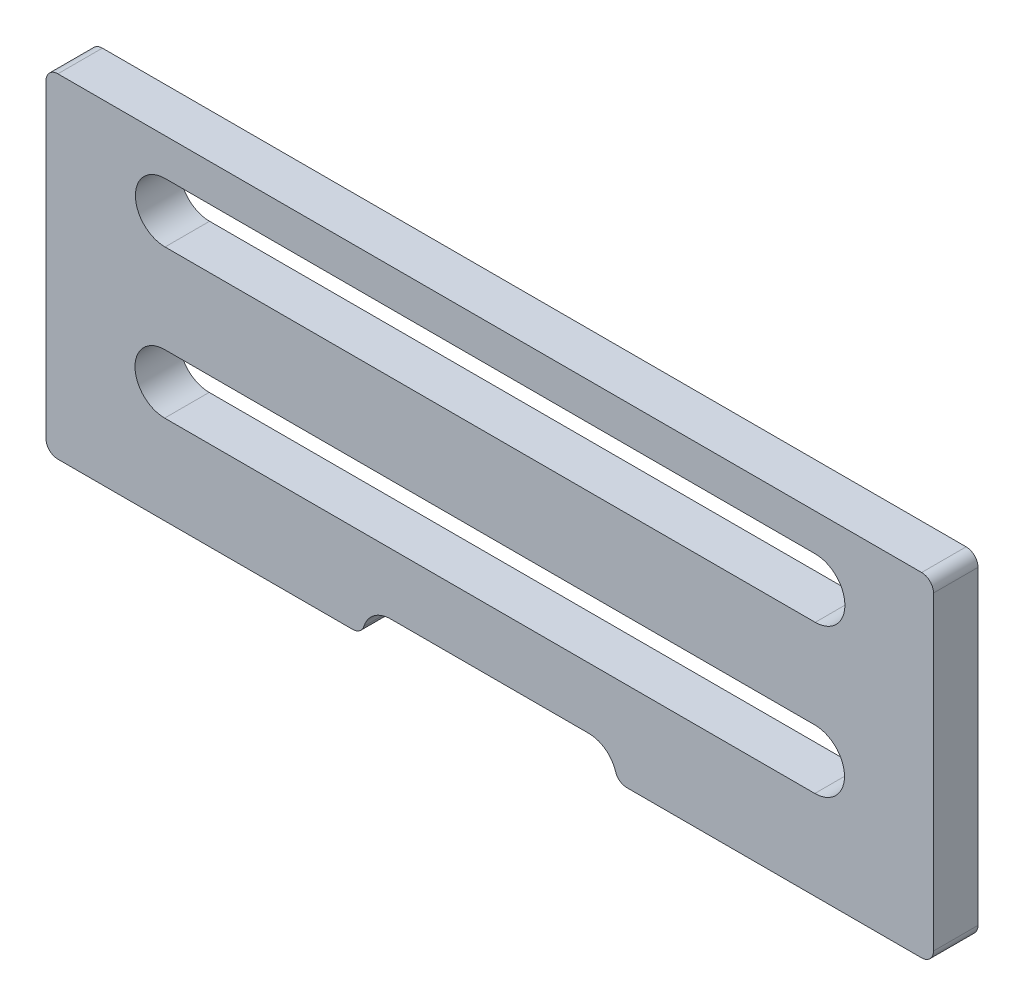
SolidWorks part; units mm, degrees
ref_plane "Front Plane" through (0, 0, 0) normal (0, 0, 1) x (1, 0, 0)
ref_plane "Top Plane" through (0, 0, 0) normal (0, 1, 0) x (1, 0, 0)
ref_plane "Right Plane" through (0, 0, 0) normal (1, 0, 0) x (0, 0, -1)
ref_plane "Plane1" through (0, 0, 4.7625) normal (0, 0, 1) x (1, 0, 0)
sketch "Sketch1" plane through (0, 0, 4.7625) normal (0, 0, 1) x (1, 0, 0)
  line L0 (-46.2192, -17.8594) -> (-14.6768, -17.8594)
  line L1 (-10.6, -14.8594) -> (10.6, -14.8594)
  line L2 (14.6768, -17.8594) -> (46.2192, -17.8594)
  line L3 (47.4892, -16.5894) -> (47.4892, 16.5894)
  line L4 (46.2192, 17.8594) -> (-46.2192, 17.8594)
  line L5 (-47.4892, 16.5894) -> (-47.4892, -16.5894)
  line L6 (34.7892, -8.3344) -> (-34.7892, -8.3344)
  line L7 (-34.7892, -1.9844) -> (34.7892, -1.9844)
  line L8 (34.8317, 7.5469) -> (-34.7467, 7.5469)
  line L9 (-34.7467, 13.8969) -> (34.8317, 13.8969)
  arc A0 (-14.6768, -17.8594) -> (-13.4642, -16.9671) centre (-14.6768, -16.5894) ccw
  arc A1 (-13.4642, -16.9671) -> (-10.6, -14.8594) centre (-10.6, -17.8594) cw
  arc A2 (10.6, -14.8594) -> (13.4642, -16.9671) centre (10.6, -17.8594) cw
  arc A3 (13.4642, -16.9671) -> (14.6768, -17.8594) centre (14.6768, -16.5894) ccw
  arc A4 (46.2192, -17.8594) -> (47.4892, -16.5894) centre (46.2192, -16.5894) ccw
  arc A5 (47.4892, 16.5894) -> (46.2192, 17.8594) centre (46.2192, 16.5894) ccw
  arc A6 (-46.2192, 17.8594) -> (-47.4892, 16.5894) centre (-46.2192, 16.5894) ccw
  arc A7 (-47.4892, -16.5894) -> (-46.2192, -17.8594) centre (-46.2192, -16.5894) ccw
  arc A8 (34.7892, -1.9844) -> (34.7892, -8.3344) centre (34.7892, -5.1594) cw
  arc A9 (-34.7892, -8.3344) -> (-34.7892, -1.9844) centre (-34.7892, -5.1594) cw
  arc A10 (34.8317, 13.8969) -> (34.8317, 7.5469) centre (34.8317, 10.7219) cw
  arc A11 (-34.7467, 7.5469) -> (-34.7467, 13.8969) centre (-34.7467, 10.7219) cw
extrude "Boss-Extrude1" add sketch "Sketch1" against normal blind 4.7625
